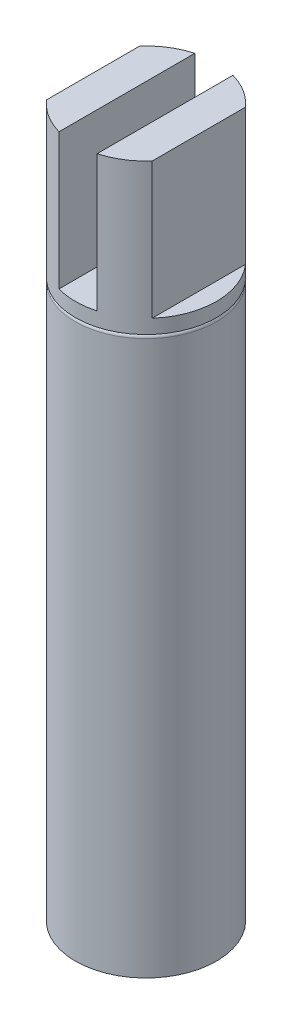
SolidWorks part; units mm, degrees
ref_plane "Front Plane" through (0, 0, 0) normal (0, 0, 1) x (1, 0, 0)
ref_plane "Top Plane" through (0, 0, 0) normal (0, 1, 0) x (1, 0, 0)
ref_plane "Right Plane" through (0, 0, 0) normal (1, 0, 0) x (0, 0, -1)
sketch "Sketch1" plane through (0, 0, 0) normal (0, 1, 0) x (1, 0, 0)
  circle A0 centre (0, 0) radius 10
  dimension "D1" = 20
extrude "Boss-Extrude1" add sketch "Sketch1" along normal blind 79
fillet "Fillet1" radius 0.5 1 edges at (0, 79, 10)
sketch "Sketch2" plane through (0, 79, 0) normal (0, 1, 0) x (1, 0, 0)
  circle A0 centre (0, 0) radius 10
  dimension "D1" = 20
extrude "Boss-Extrude2" add sketch "Sketch2" along normal blind 2
sketch "Sketch3" plane through (0, 81, 0) normal (0, 1, 0) x (1, 0, 0)
  line L0 (-7.5, 6.6144) -> (-7.5, -6.6144)
  line L1 (-2.7, 9.6286) -> (-2.7, -9.6286)
  line L2 (2.7, 9.6286) -> (2.7, -9.6286)
  line L3 (7.5, 6.6144) -> (7.5, -6.6144)
  line L4 (-2.7, 0) -> (2.7, 0) construction
  circle A0 centre (0, 0) radius 10 construction
  circle A1 centre (0, 0) radius 10
  point P12 (0, 0)
  circle M1 centre (0, 0) radius 10
  dimension "D1" = 4.8
  dimension "D2" = 4.8
  dimension "D3" = 5.4
extrude "Boss-Extrude3" add sketch "Sketch3" along normal blind 19.3 contours L1 L0 M1 | L3 L2 M1
